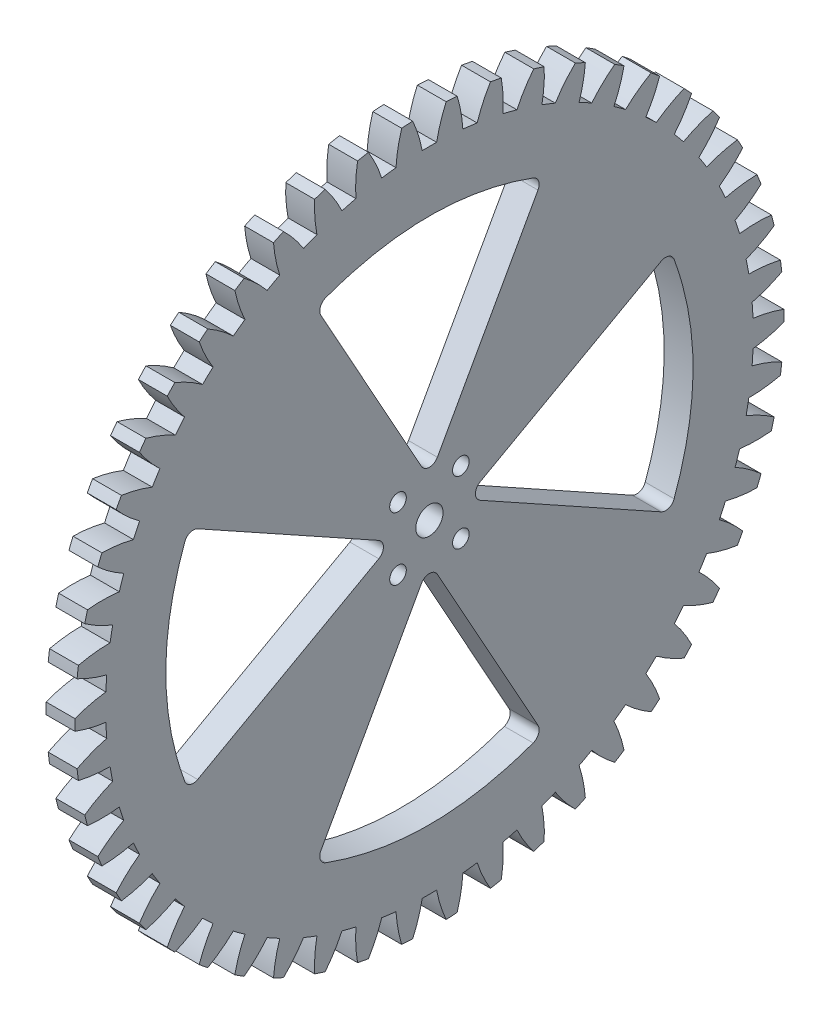
SolidWorks part; units mm, degrees
ref_plane "Plane1" through (0, 0, 0) normal (0, 0, 1) x (1, 0, 0)
ref_plane "Plane2" through (0, 0, 0) normal (0, 1, 0) x (1, 0, 0)
ref_plane "Plane3" through (0, 0, 0) normal (1, 0, 0) x (0, 0, -1)
sketch "HoldingSke" plane through (0, 0, 0) normal (0, 1, 0) x (1, 0, 0)
  line L0 (0, 0) -> (0.2143, -0.2553)
  line L1 (-15, 0) -> (100, 0) construction
  line L2 (0, 0) -> (-2.1039, 2.3779)
  line L3 (0, 0) -> (-11.863, 4.5341)
  line L4 (0, 0) -> (5.5511, 6.6156)
  line L5 (0, 0) -> (-46.8476, -17.4728)
  line L6 (0, 0) -> (-5.2639, -3.5516)
  line L7 (-2.1039, 2.3779) -> (8.6587, 51.2062)
  line L8 (-76.2, 54.61) -> (-75.2, 54.61)
  line L9 (-67.7845, 28.3722) -> (-49.3413, 33.142)
  line L10 (-76.2, 71.12) -> (104.1128, 71.12)
  line L11 (0, 0) -> (-6.35, 0)
  line L12 (-76.2, 101.6) -> (-76.093, 101.6)
  line L13 (24.9733, 27.94) -> (52.9518, 28.4284)
  line L14 (24.9733, 27.94) -> (24.9743, 27.94)
  line L15 (24.9733, 27.94) -> (100.4006, 29.5858)
  line L16 (-63.627, -3) -> (-12.827, -3)
  circle A0 centre (0, 0) radius 3
  circle A1 centre (0, 0) radius 37.5
  circle A2 centre (0, 0) radius 37.5
  circle A3 centre (0, 0) radius 3
  dimension "MHD" = 75
  dimension "Hub_dia" = 75
  dimension "Bore" = 6
  dimension "MBD" = 6
  dimension "Num_teeth" = 50
  dimension "Pitch" = 0.3333
  dimension "Overall_len" = 50
  dimension "Show_teeth" = 50
  dimension "Thickness" = 6.35
  dimension "OAL" = 50.0004
  dimension "T_dim" = 1
  dimension "Ap" = 14.5
  dimension "H" = 19.05
  dimension "Pitch_radius" = 180.3128
  dimension "Width" = 6.35
  dimension "Backlash" = 0.107
  dimension "Addendum_fac" = 1
  dimension "Dedendum_fac" = 1.25
  dimension "Clearance_fac" = 0.25
  dimension "Dedendum_add" = 0.001
  dimension "Module" = 3
sketch "BasProSke" plane through (0, 0, 0) normal (0, 1, 0) x (1, 0, 0)
  line L0 (-10, 0) -> (60, 0) construction
  line L1 (0, 0) -> (0, 78)
  line L2 (0, 0) -> (6.35, 0)
  line L3 (6.35, 0) -> (6.35, 78)
  line L4 (6.35, 78) -> (0, 78)
  dimension "Thickness" = 6.35
  dimension "Diameter" = 156
revolve "Base-Revolve" add sketch "BasProSke" angle 360 about L0
sketch "TooCutSke" plane through (0, 0, 0) normal (1, 0, 0) x (0, 0, -1)
  line L1 (0, 0) -> (0, 107) construction
  line L2 (0, 0) -> (-2.543, 74.9569) construction
  line L3 (0, 0) -> (-9.4146, 149.6414) construction
  line L4 (-2.543, 74.9569) -> (-4.7073, 74.8207) construction
  arc A0 (1.5844, 71.2314) -> (-1.5844, 71.2314) centre (0, 0) ccw
  arc A1 (3.6968, 77.9378) -> (-3.6968, 77.9378) centre (0, 0) ccw
  circle A2 centre (0, 0) radius 75 construction
  circle A3 centre (0, 0) radius 72.6111 construction
  arc A4 (-1.5844, 71.2314) -> (-3.6968, 77.9378) centre (-31.0576, 65.6338) ccw
  arc A5 (3.6968, 77.9378) -> (1.5844, 71.2314) centre (31.0576, 65.6338) ccw
  dimension "Root_dia" = 142.498
  dimension "Overcut_dia" = 156.0508
  dimension "Pitch_dia" = 150
  dimension "Base_dia" = 145.2221
  dimension "Flank_rad" = 30
  dimension "Half_ang" = 3.6
  dimension "Half_CT" = 2.1686
extrude "ToothCut" cut sketch "TooCutSke" along normal through all
fillet "Breaks" [suppressed] radius 0.06
fillet "RootFillets" [suppressed] radius 0.751
pattern_circular "TeethCuts" count 50 over 360 about axis through (0, 0, 0) along (1, 0, 0) of "ToothCut", "RootFillets", "Breaks"
sketch "HubNeaOneSke" plane through (0, 0, 0) normal (-1, 0, 0) x (0, 0, 1)
  circle A0 centre (0, 0) radius 37.5
  dimension "Diameter" = 75
extrude "HubNearOne" [suppressed] add sketch "HubNeaOneSke" along normal blind 43.6504
sketch "HubNeaBotSke" plane through (0, 0, 0) normal (-1, 0, 0) x (0, 0, 1)
  circle A0 centre (0, 0) radius 37.5
  dimension "Diameter" = 75
extrude "HubNearBoth" [suppressed] add sketch "HubNeaBotSke" along normal blind 21.8252
ref_plane "FarPln" through (6.35, 0, 0) normal (1, 0, 0) x (0, 0, -1)
sketch "HubFarSke" plane through (6.35, 0, 0) normal (1, 0, 0) x (0, 0, -1)
  circle A0 centre (0, 0) radius 37.5
  dimension "Diameter" = 75
extrude "HubFar" [suppressed] add sketch "HubFarSke" along normal blind 21.8252
sketch "BorSke" plane through (0, 0, 0) normal (1, 0, 0) x (0, 0, -1)
  circle A0 centre (0, 0) radius 3
  dimension "Diameter" = 6
extrude "Bore" cut sketch "BorSke" along normal mid plane 100.0008
sketch "KeySke" plane through (0, 0, 0) normal (1, 0, 0) x (0, 0, -1)
  line L0 (-1, 0) -> (-1, 4)
  line L1 (-1, 4) -> (1, 4)
  line L2 (1, 4) -> (1, 0)
  line L3 (0, 0) -> (0, 34) construction
  line L4 (-1, 0) -> (1, 0)
  dimension "Offset" = 4
  dimension "Width" = 2
extrude "Keyway" [suppressed] cut sketch "KeySke" along normal mid plane 100.0008
pattern_circular "Keyway2" [suppressed] count 2 every 90 about axis through (-10, 0, 0) along (1, 0, 0)
sketch "Esquisse1" plane through (0, 0, 0) normal (-1, 0, 0) x (0, 0, 1)
  circle A0 centre (6.9148, 6.9148) radius 1.83
  dimension "D1" = 3.66
extrude "Enlèv. mat.-Extru.1" cut sketch "Esquisse1" against normal up to next
pattern_circular "Répétition circulaire1" count 4 every 90 about axis through (0, 0, 0) along (1, 0, 0) of "Enlèv. mat.-Extru.1"
sketch "Esquisse2" plane through (6.35, 0, 0) normal (1, 0, 0) x (0, 0, -1)
  line L0 (-53, 25) -> (-8, 0)
  line L1 (-8, 0) -> (-53, -25)
  line L2 (-53, -25) -> (-53, 25) construction
  line L3 (-53, 0) -> (-8, 0) construction
  line L4 (50, 0) -> (-50, 0) construction
  circle A0 centre (0, 0) radius 3 construction
  spline S0 degree 2 poles (-53, 25) (-63, 0) (-53, -25) knots 0 0 0 1 1 1
  dimension "D4" = 8
  dimension "D1" = 45
  dimension "D2" = 50
  dimension "D3" = 5
extrude "Enlèv. mat.-Extru.2" cut sketch "Esquisse2" against normal up to next
fillet "Congé1" radius 2 3 edges at (3.175, -25, 53) (3.175, 25, 53) (3.175, 0, 8)
pattern_circular "Répétition circulaire2" count 4 over 360 about axis through (6.35, 0, 0) along (-1, 0, 0) of "Congé1", "Enlèv. mat.-Extru.2"
sketch "Esquisse3" plane through (6.35, 0, 0) normal (1, 0, 0) x (0, 0, -1)
  arc A200 (-77.9906, -1.2138) -> (-71.1903, -2.8913) centre (-67.4544, 26.8751) ccw
  arc A201 (-71.1903, -2.8913) -> (-70.9913, -6.054) centre (0, 0) ccw
  arc A202 (-70.9913, -6.054) -> (-77.5277, -8.5706) centre (-63.5541, -35.1175) ccw
  arc A203 (-77.5277, -8.5706) -> (-77.2234, -10.9791) centre (0, 0) ccw
  arc A204 (-77.2234, -10.9791) -> (-70.2666, -11.7911) centre (-70.2908, 18.2089) ccw
  arc A205 (-70.2666, -11.7911) -> (-69.6728, -14.9038) centre (0, 0) ccw
  arc A206 (-69.6728, -14.9038) -> (-75.8422, -18.2198) centre (-58.6516, -42.806) ccw
  arc A207 (-75.8422, -18.2198) -> (-75.2385, -20.5711) centre (0, 0) ccw
  arc A208 (-75.2385, -20.5711) -> (-68.2347, -20.5048) centre (-72.0188, 9.2556) ccw
  arc A209 (-68.2347, -20.5048) -> (-67.2554, -23.5186) centre (0, 0) ccw
  arc A210 (-67.2554, -23.5186) -> (-72.9606, -27.5817) centre (-52.8241, -49.8195) ccw
  arc A211 (-72.9606, -27.5817) -> (-72.0669, -29.8388) centre (0, 0) ccw
  arc A212 (-72.0669, -29.8388) -> (-65.1267, -28.8952) centre (-72.6109, 0.1563) ccw
  arc A213 (-65.1267, -28.8952) -> (-63.7775, -31.7625) centre (0, 0) ccw
  arc A214 (-63.7775, -31.7625) -> (-68.9284, -36.5086) centre (-46.1635, -56.0473) ccw
  arc A215 (-68.9284, -36.5086) -> (-67.7589, -38.6359) centre (0, 0) ccw
  arc A216 (-67.7589, -38.6359) -> (-60.9916, -36.8299) centre (-72.0579, -8.9455) ccw
  arc A217 (-60.9916, -36.8299) -> (-59.2937, -39.5055) centre (0, 0) ccw
  arc A218 (-59.2937, -39.5055) -> (-63.8091, -44.8597) centre (-38.7749, -61.3911) ccw
  arc A219 (-63.8091, -44.8597) -> (-62.3822, -46.8237) centre (0, 0) ccw
  arc A220 (-62.3822, -46.8237) -> (-55.8947, -44.1838) centre (-70.3686, -17.9063) ccw
  arc A221 (-55.8947, -44.1838) -> (-53.8748, -46.6254) centre (0, 0) ccw
  arc A222 (-53.8748, -46.6254) -> (-57.6836, -52.5034) centre (-30.7748, -65.7668) ccw
  arc A223 (-57.6836, -52.5034) -> (-56.0218, -54.273) centre (0, 0) ccw
  arc A224 (-56.0218, -54.273) -> (-49.9162, -50.8408) centre (-67.5694, -26.5846) ccw
  arc A225 (-49.9162, -50.8408) -> (-47.6062, -53.0101) centre (0, 0) ccw
  arc A226 (-47.6062, -53.0101) -> (-50.6483, -59.319) centre (-22.2894, -69.1054) ccw
  arc A227 (-50.6483, -59.319) -> (-48.7778, -60.8665) centre (0, 0) ccw
  arc A228 (-48.7778, -60.8665) -> (-43.1506, -56.6961) centre (-63.7047, -34.8436) ccw
  arc A229 (-43.1506, -56.6961) -> (-40.5869, -58.5587) centre (0, 0) ccw
  arc A230 (-40.5869, -58.5587) -> (-42.8143, -65.1992) centre (-13.4524, -71.354) ccw
  arc A231 (-42.8143, -65.1992) -> (-40.7646, -66.5) centre (0, 0) ccw
  arc A232 (-40.7646, -66.5) -> (-35.7044, -61.6572) centre (-58.8353, -42.5532) ccw
  arc A233 (-35.7044, -61.6572) -> (-32.9275, -63.1838) centre (0, 0) ccw
  arc A234 (-32.9275, -63.1838) -> (-34.3051, -70.0511) centre (-4.4033, -72.4774) ccw
  arc A235 (-34.3051, -70.0511) -> (-32.1085, -71.0848) centre (0, 0) ccw
  arc A236 (-32.1085, -71.0848) -> (-27.6952, -65.646) centre (-53.038, -49.5917) ccw
  arc A237 (-27.6952, -65.646) -> (-24.7488, -66.8125) centre (0, 0) ccw
  arc A238 (-24.7488, -66.8125) -> (-25.2548, -73.7983) centre (4.7152, -72.4578) ccw
  arc A239 (-25.2548, -73.7983) -> (-22.946, -74.5485) centre (0, 0) ccw
  arc A240 (-22.946, -74.5485) -> (-19.2492, -68.5995) centre (-46.4043, -55.8481) ccw
  arc A241 (-19.2492, -68.5995) -> (-16.1799, -69.3876) centre (0, 0) ccw
  arc A242 (-16.1799, -69.3876) -> (-15.8063, -76.3817) centre (13.7594, -71.2955) ccw
  arc A243 (-15.8063, -76.3817) -> (-13.4217, -76.8366) centre (0, 0) ccw
  arc A244 (-13.4217, -76.8366) -> (-10.4996, -70.4711) centre (-39.0388, -61.2237) ccw
  arc A245 (-10.4996, -70.4711) -> (-7.3557, -70.8683) centre (0, 0) ccw
  arc A246 (-7.3557, -70.8683) -> (-6.1085, -77.7604) centre (22.5866, -69.0088) ccw
  arc A247 (-6.1085, -77.7604) -> (-3.6856, -77.9129) centre (0, 0) ccw
  arc A248 (-3.6856, -77.9129) -> (-1.5844, -71.2314) centre (-31.0576, -65.6338) ccw
  arc A249 (-1.5844, -71.2314) -> (1.5844, -71.2314) centre (0, 0) ccw
  arc A250 (1.5844, -71.2314) -> (3.6856, -77.9129) centre (31.0576, -65.6338) ccw
  arc A251 (3.6856, -77.9129) -> (6.1085, -77.7604) centre (0, 0) ccw
  arc A252 (6.1085, -77.7604) -> (7.3557, -70.8683) centre (-22.5866, -69.0088) ccw
  arc A253 (7.3557, -70.8683) -> (10.4996, -70.4711) centre (0, 0) ccw
  arc A254 (10.4996, -70.4711) -> (13.4217, -76.8366) centre (39.0388, -61.2237) ccw
  arc A255 (13.4217, -76.8366) -> (15.8063, -76.3817) centre (0, 0) ccw
  arc A256 (15.8063, -76.3817) -> (16.1799, -69.3876) centre (-13.7594, -71.2955) ccw
  arc A257 (16.1799, -69.3876) -> (19.2492, -68.5995) centre (0, 0) ccw
  arc A258 (19.2492, -68.5995) -> (22.946, -74.5485) centre (46.4043, -55.8481) ccw
  arc A259 (22.946, -74.5485) -> (25.2548, -73.7983) centre (0, 0) ccw
  arc A260 (25.2548, -73.7983) -> (24.7488, -66.8125) centre (-4.7152, -72.4578) ccw
  arc A261 (24.7488, -66.8125) -> (27.6952, -65.646) centre (0, 0) ccw
  arc A262 (27.6952, -65.646) -> (32.1085, -71.0848) centre (53.038, -49.5917) ccw
  arc A263 (32.1085, -71.0848) -> (34.3051, -70.0511) centre (0, 0) ccw
  arc A264 (34.3051, -70.0511) -> (32.9275, -63.1838) centre (4.4033, -72.4774) ccw
  arc A265 (32.9275, -63.1838) -> (35.7044, -61.6572) centre (0, 0) ccw
  arc A266 (35.7044, -61.6572) -> (40.7646, -66.5) centre (58.8353, -42.5532) ccw
  arc A267 (40.7646, -66.5) -> (42.8143, -65.1992) centre (0, 0) ccw
  arc A268 (42.8143, -65.1992) -> (40.5869, -58.5587) centre (13.4524, -71.354) ccw
  arc A269 (40.5869, -58.5587) -> (43.1506, -56.6961) centre (0, 0) ccw
  arc A270 (43.1506, -56.6961) -> (48.7778, -60.8665) centre (63.7047, -34.8436) ccw
  arc A271 (48.7778, -60.8665) -> (50.6483, -59.319) centre (0, 0) ccw
  arc A272 (50.6483, -59.319) -> (47.6062, -53.0101) centre (22.2894, -69.1054) ccw
  arc A273 (47.6062, -53.0101) -> (49.9162, -50.8408) centre (0, 0) ccw
  arc A274 (49.9162, -50.8408) -> (56.0218, -54.273) centre (67.5694, -26.5846) ccw
  arc A275 (56.0218, -54.273) -> (57.6836, -52.5034) centre (0, 0) ccw
  arc A276 (57.6836, -52.5034) -> (53.8748, -46.6254) centre (30.7748, -65.7668) ccw
  arc A277 (53.8748, -46.6254) -> (55.8947, -44.1838) centre (0, 0) ccw
  arc A278 (55.8947, -44.1838) -> (62.3822, -46.8237) centre (70.3686, -17.9063) ccw
  arc A279 (62.3822, -46.8237) -> (63.8091, -44.8597) centre (0, 0) ccw
  arc A280 (63.8091, -44.8597) -> (59.2937, -39.5055) centre (38.7749, -61.3911) ccw
  arc A281 (59.2937, -39.5055) -> (60.9916, -36.8299) centre (0, 0) ccw
  arc A282 (60.9916, -36.8299) -> (67.7589, -38.6359) centre (72.0579, -8.9455) ccw
  arc A283 (67.7589, -38.6359) -> (68.9284, -36.5086) centre (0, 0) ccw
  arc A284 (68.9284, -36.5086) -> (63.7775, -31.7625) centre (46.1635, -56.0473) ccw
  arc A285 (63.7775, -31.7625) -> (65.1267, -28.8952) centre (0, 0) ccw
  arc A286 (65.1267, -28.8952) -> (72.0669, -29.8388) centre (72.6109, 0.1563) ccw
  arc A287 (72.0669, -29.8388) -> (72.9606, -27.5817) centre (0, 0) ccw
  arc A288 (72.9606, -27.5817) -> (67.2554, -23.5186) centre (52.8241, -49.8195) ccw
  arc A289 (67.2554, -23.5186) -> (68.2347, -20.5048) centre (0, 0) ccw
  arc A290 (68.2347, -20.5048) -> (75.2385, -20.5711) centre (72.0188, 9.2556) ccw
  arc A291 (75.2385, -20.5711) -> (75.8422, -18.2198) centre (0, 0) ccw
  arc A292 (75.8422, -18.2198) -> (69.6728, -14.9038) centre (58.6516, -42.806) ccw
  arc A293 (69.6728, -14.9038) -> (70.2666, -11.7911) centre (0, 0) ccw
  arc A294 (70.2666, -11.7911) -> (77.2234, -10.9791) centre (70.2908, 18.2089) ccw
  arc A295 (77.2234, -10.9791) -> (77.5277, -8.5706) centre (0, 0) ccw
  arc A296 (77.5277, -8.5706) -> (70.9913, -6.054) centre (63.5541, -35.1175) ccw
  arc A297 (70.9913, -6.054) -> (71.1903, -2.8913) centre (0, 0) ccw
  arc A298 (71.1903, -2.8913) -> (77.9906, -1.2138) centre (67.4544, 26.8751) ccw
  arc A299 (77.9906, -1.2138) -> (77.9906, 1.2138) centre (0, 0) ccw
  arc A300 (77.9906, 1.2138) -> (71.1903, 2.8913) centre (67.4544, -26.8751) ccw
  arc A301 (71.1903, 2.8913) -> (70.9913, 6.054) centre (0, 0) ccw
  arc A302 (70.9913, 6.054) -> (77.5277, 8.5706) centre (63.5541, 35.1175) ccw
  arc A303 (77.5277, 8.5706) -> (77.2234, 10.9791) centre (0, 0) ccw
  arc A304 (77.2234, 10.9791) -> (70.2666, 11.7911) centre (70.2908, -18.2089) ccw
  arc A305 (70.2666, 11.7911) -> (69.6728, 14.9038) centre (0, 0) ccw
  arc A306 (69.6728, 14.9038) -> (75.8422, 18.2198) centre (58.6516, 42.806) ccw
  arc A307 (75.8422, 18.2198) -> (75.2385, 20.5711) centre (0, 0) ccw
  arc A308 (75.2385, 20.5711) -> (68.2347, 20.5048) centre (72.0188, -9.2556) ccw
  arc A309 (68.2347, 20.5048) -> (67.2554, 23.5186) centre (0, 0) ccw
  arc A310 (67.2554, 23.5186) -> (72.9606, 27.5817) centre (52.8241, 49.8195) ccw
  arc A311 (72.9606, 27.5817) -> (72.0669, 29.8388) centre (0, 0) ccw
  arc A312 (72.0669, 29.8388) -> (65.1267, 28.8952) centre (72.6109, -0.1563) ccw
  arc A313 (65.1267, 28.8952) -> (63.7775, 31.7625) centre (0, 0) ccw
  arc A314 (63.7775, 31.7625) -> (68.9284, 36.5086) centre (46.1635, 56.0473) ccw
  arc A315 (68.9284, 36.5086) -> (67.7589, 38.6359) centre (0, 0) ccw
  arc A316 (67.7589, 38.6359) -> (60.9916, 36.8299) centre (72.0579, 8.9455) ccw
  arc A317 (60.9916, 36.8299) -> (59.2937, 39.5055) centre (0, 0) ccw
  arc A318 (59.2937, 39.5055) -> (63.8091, 44.8597) centre (38.7749, 61.3911) ccw
  arc A319 (63.8091, 44.8597) -> (62.3822, 46.8237) centre (0, 0) ccw
  arc A320 (62.3822, 46.8237) -> (55.8947, 44.1838) centre (70.3686, 17.9063) ccw
  arc A321 (55.8947, 44.1838) -> (53.8748, 46.6254) centre (0, 0) ccw
  arc A322 (53.8748, 46.6254) -> (57.6836, 52.5034) centre (30.7748, 65.7668) ccw
  arc A323 (57.6836, 52.5034) -> (56.0218, 54.273) centre (0, 0) ccw
  arc A324 (56.0218, 54.273) -> (49.9162, 50.8408) centre (67.5694, 26.5846) ccw
  arc A325 (49.9162, 50.8408) -> (47.6062, 53.0101) centre (0, 0) ccw
  arc A326 (47.6062, 53.0101) -> (50.6483, 59.319) centre (22.2894, 69.1054) ccw
  arc A327 (50.6483, 59.319) -> (48.7778, 60.8665) centre (0, 0) ccw
  arc A328 (48.7778, 60.8665) -> (43.1506, 56.6961) centre (63.7047, 34.8436) ccw
  arc A329 (43.1506, 56.6961) -> (40.5869, 58.5587) centre (0, 0) ccw
  arc A330 (40.5869, 58.5587) -> (42.8143, 65.1992) centre (13.4524, 71.354) ccw
  arc A331 (42.8143, 65.1992) -> (40.7646, 66.5) centre (0, 0) ccw
  arc A332 (40.7646, 66.5) -> (35.7044, 61.6572) centre (58.8353, 42.5532) ccw
  arc A333 (35.7044, 61.6572) -> (32.9275, 63.1838) centre (0, 0) ccw
  arc A334 (32.9275, 63.1838) -> (34.3051, 70.0511) centre (4.4033, 72.4774) ccw
  arc A335 (34.3051, 70.0511) -> (32.1085, 71.0848) centre (0, 0) ccw
  arc A336 (32.1085, 71.0848) -> (27.6952, 65.646) centre (53.038, 49.5917) ccw
  arc A337 (27.6952, 65.646) -> (24.7488, 66.8125) centre (0, 0) ccw
  arc A338 (24.7488, 66.8125) -> (25.2548, 73.7983) centre (-4.7152, 72.4578) ccw
  arc A339 (25.2548, 73.7983) -> (22.946, 74.5485) centre (0, 0) ccw
  arc A340 (22.946, 74.5485) -> (19.2492, 68.5995) centre (46.4043, 55.8481) ccw
  arc A341 (19.2492, 68.5995) -> (16.1799, 69.3876) centre (0, 0) ccw
  arc A342 (16.1799, 69.3876) -> (15.8063, 76.3817) centre (-13.7594, 71.2955) ccw
  arc A343 (15.8063, 76.3817) -> (13.4217, 76.8366) centre (0, 0) ccw
  arc A344 (13.4217, 76.8366) -> (10.4996, 70.4711) centre (39.0388, 61.2237) ccw
  arc A345 (10.4996, 70.4711) -> (7.3557, 70.8683) centre (0, 0) ccw
  arc A346 (7.3557, 70.8683) -> (6.1085, 77.7604) centre (-22.5866, 69.0088) ccw
  arc A347 (6.1085, 77.7604) -> (3.6856, 77.9129) centre (0, 0) ccw
  arc A348 (3.6856, 77.9129) -> (1.5844, 71.2314) centre (31.0576, 65.6338) ccw
  arc A349 (1.5844, 71.2314) -> (-1.5844, 71.2314) centre (0, 0) ccw
  arc A350 (-1.5844, 71.2314) -> (-3.6856, 77.9129) centre (-31.0576, 65.6338) ccw
  arc A351 (-3.6856, 77.9129) -> (-6.1085, 77.7604) centre (0, 0) ccw
  arc A352 (-6.1085, 77.7604) -> (-7.3557, 70.8683) centre (22.5866, 69.0088) ccw
  arc A353 (-7.3557, 70.8683) -> (-10.4996, 70.4711) centre (0, 0) ccw
  arc A354 (-10.4996, 70.4711) -> (-13.4217, 76.8366) centre (-39.0388, 61.2237) ccw
  arc A355 (-13.4217, 76.8366) -> (-15.8063, 76.3817) centre (0, 0) ccw
  arc A356 (-15.8063, 76.3817) -> (-16.1799, 69.3876) centre (13.7594, 71.2955) ccw
  arc A357 (-16.1799, 69.3876) -> (-19.2492, 68.5995) centre (0, 0) ccw
  arc A358 (-19.2492, 68.5995) -> (-22.946, 74.5485) centre (-46.4043, 55.8481) ccw
  arc A359 (-22.946, 74.5485) -> (-25.2548, 73.7983) centre (0, 0) ccw
  arc A360 (-25.2548, 73.7983) -> (-24.7488, 66.8125) centre (4.7152, 72.4578) ccw
  arc A361 (-24.7488, 66.8125) -> (-27.6952, 65.646) centre (0, 0) ccw
  arc A362 (-27.6952, 65.646) -> (-32.1085, 71.0848) centre (-53.038, 49.5917) ccw
  arc A363 (-32.1085, 71.0848) -> (-34.3051, 70.0511) centre (0, 0) ccw
  arc A364 (-34.3051, 70.0511) -> (-32.9275, 63.1838) centre (-4.4033, 72.4774) ccw
  arc A365 (-32.9275, 63.1838) -> (-35.7044, 61.6572) centre (0, 0) ccw
  arc A366 (-35.7044, 61.6572) -> (-40.7646, 66.5) centre (-58.8353, 42.5532) ccw
  arc A367 (-40.7646, 66.5) -> (-42.8143, 65.1992) centre (0, 0) ccw
  arc A368 (-42.8143, 65.1992) -> (-40.5869, 58.5587) centre (-13.4524, 71.354) ccw
  arc A369 (-40.5869, 58.5587) -> (-43.1506, 56.6961) centre (0, 0) ccw
  arc A370 (-43.1506, 56.6961) -> (-48.7778, 60.8665) centre (-63.7047, 34.8436) ccw
  arc A371 (-48.7778, 60.8665) -> (-50.6483, 59.319) centre (0, 0) ccw
  arc A372 (-50.6483, 59.319) -> (-47.6062, 53.0101) centre (-22.2894, 69.1054) ccw
  arc A373 (-47.6062, 53.0101) -> (-49.9162, 50.8408) centre (0, 0) ccw
  arc A374 (-49.9162, 50.8408) -> (-56.0218, 54.273) centre (-67.5694, 26.5846) ccw
  arc A375 (-56.0218, 54.273) -> (-57.6836, 52.5034) centre (0, 0) ccw
  arc A376 (-57.6836, 52.5034) -> (-53.8748, 46.6254) centre (-30.7748, 65.7668) ccw
  arc A377 (-53.8748, 46.6254) -> (-55.8947, 44.1838) centre (0, 0) ccw
  arc A378 (-55.8947, 44.1838) -> (-62.3822, 46.8237) centre (-70.3686, 17.9063) ccw
  arc A379 (-62.3822, 46.8237) -> (-63.8091, 44.8597) centre (0, 0) ccw
  arc A380 (-63.8091, 44.8597) -> (-59.2937, 39.5055) centre (-38.7749, 61.3911) ccw
  arc A381 (-59.2937, 39.5055) -> (-60.9916, 36.8299) centre (0, 0) ccw
  arc A382 (-60.9916, 36.8299) -> (-67.7589, 38.6359) centre (-72.0579, 8.9455) ccw
  arc A383 (-67.7589, 38.6359) -> (-68.9284, 36.5086) centre (0, 0) ccw
  arc A384 (-68.9284, 36.5086) -> (-63.7775, 31.7625) centre (-46.1635, 56.0473) ccw
  arc A385 (-63.7775, 31.7625) -> (-65.1267, 28.8952) centre (0, 0) ccw
  arc A386 (-65.1267, 28.8952) -> (-72.0669, 29.8388) centre (-72.6109, -0.1563) ccw
  arc A387 (-72.0669, 29.8388) -> (-72.9606, 27.5817) centre (0, 0) ccw
  arc A388 (-72.9606, 27.5817) -> (-67.2554, 23.5186) centre (-52.8241, 49.8195) ccw
  arc A389 (-67.2554, 23.5186) -> (-68.2347, 20.5048) centre (0, 0) ccw
  arc A390 (-68.2347, 20.5048) -> (-75.2385, 20.5711) centre (-72.0188, -9.2556) ccw
  arc A391 (-75.2385, 20.5711) -> (-75.8422, 18.2198) centre (0, 0) ccw
  arc A392 (-75.8422, 18.2198) -> (-69.6728, 14.9038) centre (-58.6516, 42.806) ccw
  arc A393 (-69.6728, 14.9038) -> (-70.2666, 11.7911) centre (0, 0) ccw
  arc A394 (-70.2666, 11.7911) -> (-77.2234, 10.9791) centre (-70.2908, -18.2089) ccw
  arc A395 (-77.2234, 10.9791) -> (-77.5277, 8.5706) centre (0, 0) ccw
  arc A396 (-77.5277, 8.5706) -> (-70.9913, 6.054) centre (-63.5541, 35.1175) ccw
  arc A397 (-70.9913, 6.054) -> (-71.1903, 2.8913) centre (0, 0) ccw
  arc A398 (-71.1903, 2.8913) -> (-77.9906, 1.2138) centre (-67.4544, -26.8751) ccw
  arc A399 (-77.9906, 1.2138) -> (-77.9906, -1.2138) centre (0, 0) ccw
  arc A400 (-77.9906, -1.2138) -> (-71.1903, -2.8913) centre (-67.4544, 26.8751) ccw
  arc A401 (-71.1903, -2.8913) -> (-70.9913, -6.054) centre (0, 0) ccw
  arc A402 (-70.9913, -6.054) -> (-77.5277, -8.5706) centre (-63.5541, -35.1175) ccw
  arc A403 (-77.5277, -8.5706) -> (-77.2234, -10.9791) centre (0, 0) ccw
  arc A404 (-77.2234, -10.9791) -> (-70.2666, -11.7911) centre (-70.2908, 18.2089) ccw
  arc A405 (-70.2666, -11.7911) -> (-69.6728, -14.9038) centre (0, 0) ccw
  arc A406 (-69.6728, -14.9038) -> (-75.8422, -18.2198) centre (-58.6516, -42.806) ccw
  arc A407 (-75.8422, -18.2198) -> (-75.2385, -20.5711) centre (0, 0) ccw
  arc A408 (-75.2385, -20.5711) -> (-68.2347, -20.5048) centre (-72.0188, 9.2556) ccw
  arc A409 (-68.2347, -20.5048) -> (-67.2554, -23.5186) centre (0, 0) ccw
  arc A410 (-67.2554, -23.5186) -> (-72.9606, -27.5817) centre (-52.8241, -49.8195) ccw
  arc A411 (-72.9606, -27.5817) -> (-72.0669, -29.8388) centre (0, 0) ccw
  arc A412 (-72.0669, -29.8388) -> (-65.1267, -28.8952) centre (-72.6109, 0.1563) ccw
  arc A413 (-65.1267, -28.8952) -> (-63.7775, -31.7625) centre (0, 0) ccw
  arc A414 (-63.7775, -31.7625) -> (-68.9284, -36.5086) centre (-46.1635, -56.0473) ccw
  arc A415 (-68.9284, -36.5086) -> (-67.7589, -38.6359) centre (0, 0) ccw
  arc A416 (-67.7589, -38.6359) -> (-60.9916, -36.8299) centre (-72.0579, -8.9455) ccw
  arc A417 (-60.9916, -36.8299) -> (-59.2937, -39.5055) centre (0, 0) ccw
  arc A418 (-59.2937, -39.5055) -> (-63.8091, -44.8597) centre (-38.7749, -61.3911) ccw
  arc A419 (-63.8091, -44.8597) -> (-62.3822, -46.8237) centre (0, 0) ccw
  arc A420 (-62.3822, -46.8237) -> (-55.8947, -44.1838) centre (-70.3686, -17.9063) ccw
  arc A421 (-55.8947, -44.1838) -> (-53.8748, -46.6254) centre (0, 0) ccw
  arc A422 (-53.8748, -46.6254) -> (-57.6836, -52.5034) centre (-30.7748, -65.7668) ccw
  arc A423 (-57.6836, -52.5034) -> (-56.0218, -54.273) centre (0, 0) ccw
  arc A424 (-56.0218, -54.273) -> (-49.9162, -50.8408) centre (-67.5694, -26.5846) ccw
  arc A425 (-49.9162, -50.8408) -> (-47.6062, -53.0101) centre (0, 0) ccw
  arc A426 (-47.6062, -53.0101) -> (-50.6483, -59.319) centre (-22.2894, -69.1054) ccw
  arc A427 (-50.6483, -59.319) -> (-48.7778, -60.8665) centre (0, 0) ccw
  arc A428 (-48.7778, -60.8665) -> (-43.1506, -56.6961) centre (-63.7047, -34.8436) ccw
  arc A429 (-43.1506, -56.6961) -> (-40.5869, -58.5587) centre (0, 0) ccw
  arc A430 (-40.5869, -58.5587) -> (-42.8143, -65.1992) centre (-13.4524, -71.354) ccw
  arc A431 (-42.8143, -65.1992) -> (-40.7646, -66.5) centre (0, 0) ccw
  arc A432 (-40.7646, -66.5) -> (-35.7044, -61.6572) centre (-58.8353, -42.5532) ccw
  arc A433 (-35.7044, -61.6572) -> (-32.9275, -63.1838) centre (0, 0) ccw
  arc A434 (-32.9275, -63.1838) -> (-34.3051, -70.0511) centre (-4.4033, -72.4774) ccw
  arc A435 (-34.3051, -70.0511) -> (-32.1085, -71.0848) centre (0, 0) ccw
  arc A436 (-32.1085, -71.0848) -> (-27.6952, -65.646) centre (-53.038, -49.5917) ccw
  arc A437 (-27.6952, -65.646) -> (-24.7488, -66.8125) centre (0, 0) ccw
  arc A438 (-24.7488, -66.8125) -> (-25.2548, -73.7983) centre (4.7152, -72.4578) ccw
  arc A439 (-25.2548, -73.7983) -> (-22.946, -74.5485) centre (0, 0) ccw
  arc A440 (-22.946, -74.5485) -> (-19.2492, -68.5995) centre (-46.4043, -55.8481) ccw
  arc A441 (-19.2492, -68.5995) -> (-16.1799, -69.3876) centre (0, 0) ccw
  arc A442 (-16.1799, -69.3876) -> (-15.8063, -76.3817) centre (13.7594, -71.2955) ccw
  arc A443 (-15.8063, -76.3817) -> (-13.4217, -76.8366) centre (0, 0) ccw
  arc A444 (-13.4217, -76.8366) -> (-10.4996, -70.4711) centre (-39.0388, -61.2237) ccw
  arc A445 (-10.4996, -70.4711) -> (-7.3557, -70.8683) centre (0, 0) ccw
  arc A446 (-7.3557, -70.8683) -> (-6.1085, -77.7604) centre (22.5866, -69.0088) ccw
  arc A447 (-6.1085, -77.7604) -> (-3.6856, -77.9129) centre (0, 0) ccw
  arc A448 (-3.6856, -77.9129) -> (-1.5844, -71.2314) centre (-31.0576, -65.6338) ccw
  arc A449 (-1.5844, -71.2314) -> (1.5844, -71.2314) centre (0, 0) ccw
  arc A450 (1.5844, -71.2314) -> (3.6856, -77.9129) centre (31.0576, -65.6338) ccw
  arc A451 (3.6856, -77.9129) -> (6.1085, -77.7604) centre (0, 0) ccw
  arc A452 (6.1085, -77.7604) -> (7.3557, -70.8683) centre (-22.5866, -69.0088) ccw
  arc A453 (7.3557, -70.8683) -> (10.4996, -70.4711) centre (0, 0) ccw
  arc A454 (10.4996, -70.4711) -> (13.4217, -76.8366) centre (39.0388, -61.2237) ccw
  arc A455 (13.4217, -76.8366) -> (15.8063, -76.3817) centre (0, 0) ccw
  arc A456 (15.8063, -76.3817) -> (16.1799, -69.3876) centre (-13.7594, -71.2955) ccw
  arc A457 (16.1799, -69.3876) -> (19.2492, -68.5995) centre (0, 0) ccw
  arc A458 (19.2492, -68.5995) -> (22.946, -74.5485) centre (46.4043, -55.8481) ccw
  arc A459 (22.946, -74.5485) -> (25.2548, -73.7983) centre (0, 0) ccw
  arc A460 (25.2548, -73.7983) -> (24.7488, -66.8125) centre (-4.7152, -72.4578) ccw
  arc A461 (24.7488, -66.8125) -> (27.6952, -65.646) centre (0, 0) ccw
  arc A462 (27.6952, -65.646) -> (32.1085, -71.0848) centre (53.038, -49.5917) ccw
  arc A463 (32.1085, -71.0848) -> (34.3051, -70.0511) centre (0, 0) ccw
  arc A464 (34.3051, -70.0511) -> (32.9275, -63.1838) centre (4.4033, -72.4774) ccw
  arc A465 (32.9275, -63.1838) -> (35.7044, -61.6572) centre (0, 0) ccw
  arc A466 (35.7044, -61.6572) -> (40.7646, -66.5) centre (58.8353, -42.5532) ccw
  arc A467 (40.7646, -66.5) -> (42.8143, -65.1992) centre (0, 0) ccw
  arc A468 (42.8143, -65.1992) -> (40.5869, -58.5587) centre (13.4524, -71.354) ccw
  arc A469 (40.5869, -58.5587) -> (43.1506, -56.6961) centre (0, 0) ccw
  arc A470 (43.1506, -56.6961) -> (48.7778, -60.8665) centre (63.7047, -34.8436) ccw
  arc A471 (48.7778, -60.8665) -> (50.6483, -59.319) centre (0, 0) ccw
  arc A472 (50.6483, -59.319) -> (47.6062, -53.0101) centre (22.2894, -69.1054) ccw
  arc A473 (47.6062, -53.0101) -> (49.9162, -50.8408) centre (0, 0) ccw
  arc A474 (49.9162, -50.8408) -> (56.0218, -54.273) centre (67.5694, -26.5846) ccw
  arc A475 (56.0218, -54.273) -> (57.6836, -52.5034) centre (0, 0) ccw
  arc A476 (57.6836, -52.5034) -> (53.8748, -46.6254) centre (30.7748, -65.7668) ccw
  arc A477 (53.8748, -46.6254) -> (55.8947, -44.1838) centre (0, 0) ccw
  arc A478 (55.8947, -44.1838) -> (62.3822, -46.8237) centre (70.3686, -17.9063) ccw
  arc A479 (62.3822, -46.8237) -> (63.8091, -44.8597) centre (0, 0) ccw
  arc A480 (63.8091, -44.8597) -> (59.2937, -39.5055) centre (38.7749, -61.3911) ccw
  arc A481 (59.2937, -39.5055) -> (60.9916, -36.8299) centre (0, 0) ccw
  arc A482 (60.9916, -36.8299) -> (67.7589, -38.6359) centre (72.0579, -8.9455) ccw
  arc A483 (67.7589, -38.6359) -> (68.9284, -36.5086) centre (0, 0) ccw
  arc A484 (68.9284, -36.5086) -> (63.7775, -31.7625) centre (46.1635, -56.0473) ccw
  arc A485 (63.7775, -31.7625) -> (65.1267, -28.8952) centre (0, 0) ccw
  arc A486 (65.1267, -28.8952) -> (72.0669, -29.8388) centre (72.6109, 0.1563) ccw
  arc A487 (72.0669, -29.8388) -> (72.9606, -27.5817) centre (0, 0) ccw
  arc A488 (72.9606, -27.5817) -> (67.2554, -23.5186) centre (52.8241, -49.8195) ccw
  arc A489 (67.2554, -23.5186) -> (68.2347, -20.5048) centre (0, 0) ccw
  arc A490 (68.2347, -20.5048) -> (75.2385, -20.5711) centre (72.0188, 9.2556) ccw
  arc A491 (75.2385, -20.5711) -> (75.8422, -18.2198) centre (0, 0) ccw
  arc A492 (75.8422, -18.2198) -> (69.6728, -14.9038) centre (58.6516, -42.806) ccw
  arc A493 (69.6728, -14.9038) -> (70.2666, -11.7911) centre (0, 0) ccw
  arc A494 (70.2666, -11.7911) -> (77.2234, -10.9791) centre (70.2908, 18.2089) ccw
  arc A495 (77.2234, -10.9791) -> (77.5277, -8.5706) centre (0, 0) ccw
  arc A496 (77.5277, -8.5706) -> (70.9913, -6.054) centre (63.5541, -35.1175) ccw
  arc A497 (70.9913, -6.054) -> (71.1903, -2.8913) centre (0, 0) ccw
  arc A498 (71.1903, -2.8913) -> (77.9906, -1.2138) centre (67.4544, 26.8751) ccw
  arc A499 (77.9906, -1.2138) -> (77.9906, 1.2138) centre (0, 0) ccw
  arc A500 (77.9906, 1.2138) -> (71.1903, 2.8913) centre (67.4544, -26.8751) ccw
  arc A501 (71.1903, 2.8913) -> (70.9913, 6.054) centre (0, 0) ccw
  arc A502 (70.9913, 6.054) -> (77.5277, 8.5706) centre (63.5541, 35.1175) ccw
  arc A503 (77.5277, 8.5706) -> (77.2234, 10.9791) centre (0, 0) ccw
  arc A504 (77.2234, 10.9791) -> (70.2666, 11.7911) centre (70.2908, -18.2089) ccw
  arc A505 (70.2666, 11.7911) -> (69.6728, 14.9038) centre (0, 0) ccw
  arc A506 (69.6728, 14.9038) -> (75.8422, 18.2198) centre (58.6516, 42.806) ccw
  arc A507 (75.8422, 18.2198) -> (75.2385, 20.5711) centre (0, 0) ccw
  arc A508 (75.2385, 20.5711) -> (68.2347, 20.5048) centre (72.0188, -9.2556) ccw
  arc A509 (68.2347, 20.5048) -> (67.2554, 23.5186) centre (0, 0) ccw
  arc A510 (67.2554, 23.5186) -> (72.9606, 27.5817) centre (52.8241, 49.8195) ccw
  arc A511 (72.9606, 27.5817) -> (72.0669, 29.8388) centre (0, 0) ccw
  arc A512 (72.0669, 29.8388) -> (65.1267, 28.8952) centre (72.6109, -0.1563) ccw
  arc A513 (65.1267, 28.8952) -> (63.7775, 31.7625) centre (0, 0) ccw
  arc A514 (63.7775, 31.7625) -> (68.9284, 36.5086) centre (46.1635, 56.0473) ccw
  arc A515 (68.9284, 36.5086) -> (67.7589, 38.6359) centre (0, 0) ccw
  arc A516 (67.7589, 38.6359) -> (60.9916, 36.8299) centre (72.0579, 8.9455) ccw
  arc A517 (60.9916, 36.8299) -> (59.2937, 39.5055) centre (0, 0) ccw
  arc A518 (59.2937, 39.5055) -> (63.8091, 44.8597) centre (38.7749, 61.3911) ccw
  arc A519 (63.8091, 44.8597) -> (62.3822, 46.8237) centre (0, 0) ccw
  arc A520 (62.3822, 46.8237) -> (55.8947, 44.1838) centre (70.3686, 17.9063) ccw
  arc A521 (55.8947, 44.1838) -> (53.8748, 46.6254) centre (0, 0) ccw
  arc A522 (53.8748, 46.6254) -> (57.6836, 52.5034) centre (30.7748, 65.7668) ccw
  arc A523 (57.6836, 52.5034) -> (56.0218, 54.273) centre (0, 0) ccw
  arc A524 (56.0218, 54.273) -> (49.9162, 50.8408) centre (67.5694, 26.5846) ccw
  arc A525 (49.9162, 50.8408) -> (47.6062, 53.0101) centre (0, 0) ccw
  arc A526 (47.6062, 53.0101) -> (50.6483, 59.319) centre (22.2894, 69.1054) ccw
  arc A527 (50.6483, 59.319) -> (48.7778, 60.8665) centre (0, 0) ccw
  arc A528 (48.7778, 60.8665) -> (43.1506, 56.6961) centre (63.7047, 34.8436) ccw
  arc A529 (43.1506, 56.6961) -> (40.5869, 58.5587) centre (0, 0) ccw
  arc A530 (40.5869, 58.5587) -> (42.8143, 65.1992) centre (13.4524, 71.354) ccw
  arc A531 (42.8143, 65.1992) -> (40.7646, 66.5) centre (0, 0) ccw
  arc A532 (40.7646, 66.5) -> (35.7044, 61.6572) centre (58.8353, 42.5532) ccw
  arc A533 (35.7044, 61.6572) -> (32.9275, 63.1838) centre (0, 0) ccw
  arc A534 (32.9275, 63.1838) -> (34.3051, 70.0511) centre (4.4033, 72.4774) ccw
  arc A535 (34.3051, 70.0511) -> (32.1085, 71.0848) centre (0, 0) ccw
  arc A536 (32.1085, 71.0848) -> (27.6952, 65.646) centre (53.038, 49.5917) ccw
  arc A537 (27.6952, 65.646) -> (24.7488, 66.8125) centre (0, 0) ccw
  arc A538 (24.7488, 66.8125) -> (25.2548, 73.7983) centre (-4.7152, 72.4578) ccw
  arc A539 (25.2548, 73.7983) -> (22.946, 74.5485) centre (0, 0) ccw
  arc A540 (22.946, 74.5485) -> (19.2492, 68.5995) centre (46.4043, 55.8481) ccw
  arc A541 (19.2492, 68.5995) -> (16.1799, 69.3876) centre (0, 0) ccw
  arc A542 (16.1799, 69.3876) -> (15.8063, 76.3817) centre (-13.7594, 71.2955) ccw
  arc A543 (15.8063, 76.3817) -> (13.4217, 76.8366) centre (0, 0) ccw
  arc A544 (13.4217, 76.8366) -> (10.4996, 70.4711) centre (39.0388, 61.2237) ccw
  arc A545 (10.4996, 70.4711) -> (7.3557, 70.8683) centre (0, 0) ccw
  arc A546 (7.3557, 70.8683) -> (6.1085, 77.7604) centre (-22.5866, 69.0088) ccw
  arc A547 (6.1085, 77.7604) -> (3.6856, 77.9129) centre (0, 0) ccw
  arc A548 (3.6856, 77.9129) -> (1.5844, 71.2314) centre (31.0576, 65.6338) ccw
  arc A549 (1.5844, 71.2314) -> (-1.5844, 71.2314) centre (0, 0) ccw
  arc A550 (-1.5844, 71.2314) -> (-3.6856, 77.9129) centre (-31.0576, 65.6338) ccw
  arc A551 (-3.6856, 77.9129) -> (-6.1085, 77.7604) centre (0, 0) ccw
  arc A552 (-6.1085, 77.7604) -> (-7.3557, 70.8683) centre (22.5866, 69.0088) ccw
  arc A553 (-7.3557, 70.8683) -> (-10.4996, 70.4711) centre (0, 0) ccw
  arc A554 (-10.4996, 70.4711) -> (-13.4217, 76.8366) centre (-39.0388, 61.2237) ccw
  arc A555 (-13.4217, 76.8366) -> (-15.8063, 76.3817) centre (0, 0) ccw
  arc A556 (-15.8063, 76.3817) -> (-16.1799, 69.3876) centre (13.7594, 71.2955) ccw
  arc A557 (-16.1799, 69.3876) -> (-19.2492, 68.5995) centre (0, 0) ccw
  arc A558 (-19.2492, 68.5995) -> (-22.946, 74.5485) centre (-46.4043, 55.8481) ccw
  arc A559 (-22.946, 74.5485) -> (-25.2548, 73.7983) centre (0, 0) ccw
  arc A560 (-25.2548, 73.7983) -> (-24.7488, 66.8125) centre (4.7152, 72.4578) ccw
  arc A561 (-24.7488, 66.8125) -> (-27.6952, 65.646) centre (0, 0) ccw
  arc A562 (-27.6952, 65.646) -> (-32.1085, 71.0848) centre (-53.038, 49.5917) ccw
  arc A563 (-32.1085, 71.0848) -> (-34.3051, 70.0511) centre (0, 0) ccw
  arc A564 (-34.3051, 70.0511) -> (-32.9275, 63.1838) centre (-4.4033, 72.4774) ccw
  arc A565 (-32.9275, 63.1838) -> (-35.7044, 61.6572) centre (0, 0) ccw
  arc A566 (-35.7044, 61.6572) -> (-40.7646, 66.5) centre (-58.8353, 42.5532) ccw
  arc A567 (-40.7646, 66.5) -> (-42.8143, 65.1992) centre (0, 0) ccw
  arc A568 (-42.8143, 65.1992) -> (-40.5869, 58.5587) centre (-13.4524, 71.354) ccw
  arc A569 (-40.5869, 58.5587) -> (-43.1506, 56.6961) centre (0, 0) ccw
  arc A570 (-43.1506, 56.6961) -> (-48.7778, 60.8665) centre (-63.7047, 34.8436) ccw
  arc A571 (-48.7778, 60.8665) -> (-50.6483, 59.319) centre (0, 0) ccw
  arc A572 (-50.6483, 59.319) -> (-47.6062, 53.0101) centre (-22.2894, 69.1054) ccw
  arc A573 (-47.6062, 53.0101) -> (-49.9162, 50.8408) centre (0, 0) ccw
  arc A574 (-49.9162, 50.8408) -> (-56.0218, 54.273) centre (-67.5694, 26.5846) ccw
  arc A575 (-56.0218, 54.273) -> (-57.6836, 52.5034) centre (0, 0) ccw
  arc A576 (-57.6836, 52.5034) -> (-53.8748, 46.6254) centre (-30.7748, 65.7668) ccw
  arc A577 (-53.8748, 46.6254) -> (-55.8947, 44.1838) centre (0, 0) ccw
  arc A578 (-55.8947, 44.1838) -> (-62.3822, 46.8237) centre (-70.3686, 17.9063) ccw
  arc A579 (-62.3822, 46.8237) -> (-63.8091, 44.8597) centre (0, 0) ccw
  arc A580 (-63.8091, 44.8597) -> (-59.2937, 39.5055) centre (-38.7749, 61.3911) ccw
  arc A581 (-59.2937, 39.5055) -> (-60.9916, 36.8299) centre (0, 0) ccw
  arc A582 (-60.9916, 36.8299) -> (-67.7589, 38.6359) centre (-72.0579, 8.9455) ccw
  arc A583 (-67.7589, 38.6359) -> (-68.9284, 36.5086) centre (0, 0) ccw
  arc A584 (-68.9284, 36.5086) -> (-63.7775, 31.7625) centre (-46.1635, 56.0473) ccw
  arc A585 (-63.7775, 31.7625) -> (-65.1267, 28.8952) centre (0, 0) ccw
  arc A586 (-65.1267, 28.8952) -> (-72.0669, 29.8388) centre (-72.6109, -0.1563) ccw
  arc A587 (-72.0669, 29.8388) -> (-72.9606, 27.5817) centre (0, 0) ccw
  arc A588 (-72.9606, 27.5817) -> (-67.2554, 23.5186) centre (-52.8241, 49.8195) ccw
  arc A589 (-67.2554, 23.5186) -> (-68.2347, 20.5048) centre (0, 0) ccw
  arc A590 (-68.2347, 20.5048) -> (-75.2385, 20.5711) centre (-72.0188, -9.2556) ccw
  arc A591 (-75.2385, 20.5711) -> (-75.8422, 18.2198) centre (0, 0) ccw
  arc A592 (-75.8422, 18.2198) -> (-69.6728, 14.9038) centre (-58.6516, 42.806) ccw
  arc A593 (-69.6728, 14.9038) -> (-70.2666, 11.7911) centre (0, 0) ccw
  arc A594 (-70.2666, 11.7911) -> (-77.2234, 10.9791) centre (-70.2908, -18.2089) ccw
  arc A595 (-77.2234, 10.9791) -> (-77.5277, 8.5706) centre (0, 0) ccw
  arc A596 (-77.5277, 8.5706) -> (-70.9913, 6.054) centre (-63.5541, 35.1175) ccw
  arc A597 (-70.9913, 6.054) -> (-71.1903, 2.8913) centre (0, 0) ccw
  arc A598 (-71.1903, 2.8913) -> (-77.9906, 1.2138) centre (-67.4544, -26.8751) ccw
  arc A599 (-77.9906, 1.2138) -> (-77.9906, -1.2138) centre (0, 0) ccw
  dimension "D1" = 0
equation "' \"Module@HoldingSke\" = 6.35"
equation "' \"Num_teeth@HoldingSke\" = 12"
equation "' \"Ap@HoldingSke\" =  20"
equation "' \"Ap@HoldingSke\" = 20"
equation "' \"Width@HoldingSke\" = 0.5 * 25.4"
equation "' \"Hub_dia@HoldingSke\"= 1 * 25.4"
equation "' \"Hub_dia@HoldingSke\" = 1 * 25.4"
equation "' \"Overall_len@HoldingSke\" = 1.0 * 25.4"
equation "' \"Bore@HoldingSke\" = 0.75 * 25.4"
equation "' \"T_dim@HoldingSke\" = 0.1 * 25.4"
equation "' \"Width@KeySke\" = 0.25 * 25.4"
equation "' \"Show_teeth@HoldingSke\" = 13"
equation "' \"Backlash@HoldingSke\" = 0.009 * 25.4"
equation "' \"Addendum_fac@HoldingSke\" = 1.0"
equation "' \"Dedendum_fac@HoldingSke\" = 1.25"
equation "' \"Dedendum_add@HoldingSke\" = 0.00005 * 25.4"
equation "' \"Clearance_fac@HoldingSke\" = 0.25"
equation "\"Pitch@HoldingSke\" = 1 / \"Module@HoldingSke\""
equation "\"Overcut_dia@TooCutSke\" = (\"Num_teeth@HoldingSke\" + 2 * \"Addendum_fac@HoldingSke\") / \"Pitch@HoldingSke\" + 0.002 * 25.4"
equation "\"Pitch_dia@TooCutSke\" = \"Num_teeth@HoldingSke\" / \"Pitch@HoldingSke\""
equation "\"Base_dia@TooCutSke\" = \"Num_teeth@HoldingSke\" / \"Pitch@HoldingSke\" * cos((\"Ap@HoldingSke\"  * 3.14159265 / 180))"
equation "\"Root_dia@TooCutSke\" = (\"Num_teeth@HoldingSke\" + 2) / \"Pitch@HoldingSke\" - 2 * (\"Addendum_fac@HoldingSke\" + \"Dedendum_fac@HoldingSke\") / \"Pitch@HoldingSke\" - \"Dedendum_add@HoldingSke\" * 2"
equation "\"Half_ang@TooCutSke\" = 180 / \"Num_teeth@HoldingSke\""
equation "\"Half_CT@TooCutSke\" = \"Num_teeth@HoldingSke\" / \"Pitch@HoldingSke\" * sin((3.14159265 / 2 / \"Num_teeth@HoldingSke\")) / 2 - 7 * \"Backlash@HoldingSke\" / 4"
equation "\"Flank_rad@TooCutSke\" = \"Num_teeth@HoldingSke\" / \"Pitch@HoldingSke\" / 5"
equation "\"Radius@RootFillets\" = \"Clearance_fac@HoldingSke\" / \"Pitch@HoldingSke\" + \"Dedendum_add@HoldingSke\""
equation "\"Break_rad@Breaks\" = 0.02 / \"Pitch@HoldingSke\""
equation "\"Thickness@HoldingSke\" = \"Width@HoldingSke\""
equation "\"OAL@HoldingSke\" = \"Thickness@HoldingSke\""
equation "\"MHD@HoldingSke\" = (\"Num_teeth@HoldingSke\" + 2) / \"Pitch@HoldingSke\" - 2 * (\"Addendum_fac@HoldingSke\" + \"Dedendum_fac@HoldingSke\")  / \"Pitch@HoldingSke\" - \"Dedendum_add@HoldingSke\" * 2"
equation "\"MBD@HoldingSke\" = (\"Num_teeth@HoldingSke\" + 2) / \"Pitch@HoldingSke\" - 2 * (\"Addendum_fac@HoldingSke\" + \"Dedendum_fac@HoldingSke\")  / \"Pitch@HoldingSke\" - \"Dedendum_add@HoldingSke\" * 2 - 0.002 * 25.4"
equation "\"MHD@HoldingSke\" = ((sgn( \"MHD@HoldingSke\" - \"Hub_dia@HoldingSke\" )-1)*( \"MHD@HoldingSke\" - \"Hub_dia@HoldingSke\" ))/-2+ \"Hub_dia@HoldingSke\""
equation "\"MBD@HoldingSke\" = ((sgn( \"MBD@HoldingSke\" - \"Bore@HoldingSke\" )-1)*( \"MBD@HoldingSke\" - \"Bore@HoldingSke\" ))/-2+ \"Bore@HoldingSke\""
equation "\"OAL@HoldingSke\" = ((sgn( \"OAL@HoldingSke\" - \"Overall_len@HoldingSke\" )+1)*( \"OAL@HoldingSke\" - \"Overall_len@HoldingSke\" ))/2 + \"Overall_len@HoldingSke\" + 0.000002 * 25.4"
equation "\"Num_teeth@TeethCuts\" = int( \"Show_teeth@HoldingSke\" ) + 1"
equation "\"Num_teeth@TeethCuts\" = ((sgn( \"Num_teeth@TeethCuts\" - \"Num_teeth@HoldingSke\" )-1)*( \"Num_teeth@TeethCuts\" - \"Num_teeth@HoldingSke\" ))/-2+ \"Num_teeth@HoldingSke\""
equation "\"Num_teeth@TeethCuts\" = ((sgn( \"Num_teeth@TeethCuts\" - 2.0)+1)*( \"Num_teeth@TeethCuts\" - 2.0))/2 +2.0"
equation "\"Angle@TeethCuts\" = 360.0 / \"Num_teeth@HoldingSke\""
equation "\"Diameter@BasProSke\" = (\"Num_teeth@HoldingSke\" + 2 * \"Addendum_fac@HoldingSke\") / \"Pitch@HoldingSke\""
equation "\"Thickness@BasProSke\"  = \"Thickness@HoldingSke\""
equation "' \"Fillet_rad@BasProSke\" =  \"Thickness@HoldingSke\" * 0.05"
equation "' \"Fillet_rad@BasProSke\" = \"Thickness@HoldingSke\" * 0.05"
equation "\"MHD@HoldingSke\" = ((sgn( \"MHD@HoldingSke\" - \"Root_dia@TooCutSke\" )-1)*( \"MHD@HoldingSke\" - \"Root_dia@TooCutSke\" ))/-2+ \"Root_dia@TooCutSke\""
equation "\"Diameter@HubNeaOneSke\" = \"MHD@HoldingSke\""
equation "\"Length@HubNearOne\" = \"OAL@HoldingSke\" - \"Thickness@BasProSke\""
equation "\"Diameter@HubNeaBotSke\" = \"MHD@HoldingSke\""
equation "\"Length@HubNearBoth\" = ( \"OAL@HoldingSke\" - \"Thickness@BasProSke\" ) / 2.0"
equation "\"Thickness@FarPln\" = \"Thickness@BasProSke\""
equation "\"Diameter@HubFarSke\" = \"MHD@HoldingSke\""
equation "\"Length@HubFar\" = ( \"OAL@HoldingSke\" - \"Thickness@BasProSke\" ) / 2.0"
equation "\"Diameter@BorSke\" = \"MBD@HoldingSke\""
equation "\"D1@Bore\" = \"OAL@HoldingSke\" * 2.0"
equation "\"D1@Keyway\" = \"OAL@HoldingSke\" * 2.0"
equation "\"Offset@KeySke\" = \"T_dim@HoldingSke\" + \"MBD@HoldingSke\" / 2.0"
